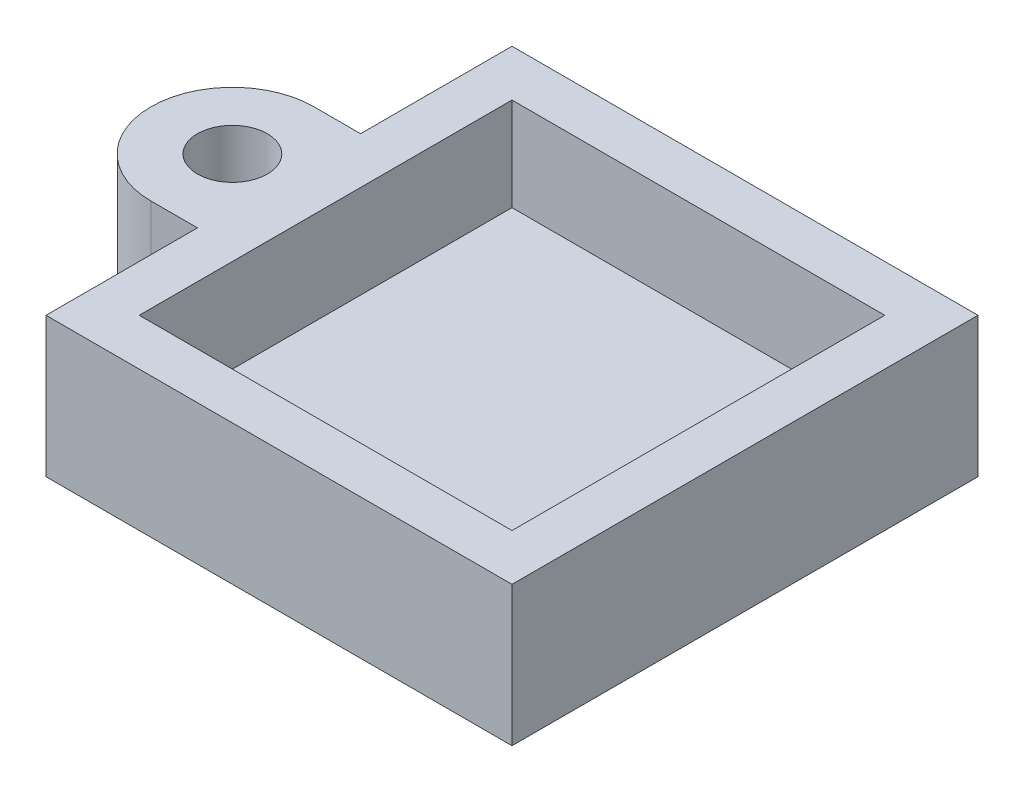
SolidWorks part; units mm, degrees
ref_plane "Front Plane" through (0, 0, 0) normal (0, 0, 1) x (1, 0, 0)
ref_plane "Top Plane" through (0, 0, 0) normal (0, 1, 0) x (1, 0, 0)
ref_plane "Right Plane" through (0, 0, 0) normal (1, 0, 0) x (0, 0, -1)
sketch "Sketch1" plane through (0, 0, 0) normal (0, 1, 0) x (1, 0, 0)
  line L0 (-2, 8) -> (-2.5, 8) construction
  line L1 (0, 0) -> (16, 0)
  line L2 (0, 0) -> (0, 16)
  line L3 (0, 16) -> (16, 16)
  line L4 (16, 0) -> (16, 16)
  line L5 (-2, 18) -> (18, 18)
  line L6 (-2, 18) -> (-2, 11.5)
  line L7 (-2, -2) -> (18, -2)
  line L8 (18, 18) -> (18, -2)
  line L9 (-2, 4.5) -> (-2, -2)
  line L10 (0, 8) -> (-0.5, 8) construction
  line L11 (-2, 8) -> (-7.5, 8) construction
  line L12 (0, 8) -> (-7.5, 8) construction
  line L13 (-4, 11.5) -> (-2, 11.5)
  line L14 (-4, 11.5) -> (-4, 4.5) construction
  line L15 (-4, 4.5) -> (-2, 4.5)
  circle A0 centre (-4, 8) radius 1.5
  arc A1 (-4, 11.5) -> (-4, 4.5) centre (-4, 8) ccw
  dimension "D7" = 3
  dimension "D9" = 7
  dimension "D1" = 16
  dimension "D2" = 16
  dimension "D3" = 2
  dimension "D4" = 2
  dimension "D5" = 2
  dimension "D6" = 2
  dimension "D8" = 2
extrude "Boss-Extrude1" add sketch "Sketch1" along normal blind 4
sketch "Sketch2" plane through (0, 0, 0) normal (0, -1, 0) x (1, 0, 0)
  line L0 (18, 2) -> (18, -18) construction
  line L1 (18, -18) -> (-2, -18) construction
  line L2 (-2, -18) -> (-2, -11.5) construction
  line L3 (-2, -11.5) -> (-4, -11.5) construction
  line L4 (-4, -4.5) -> (-2, -4.5) construction
  line L5 (-2, -4.5) -> (-2, 2) construction
  line L6 (-2, 2) -> (18, 2) construction
  line L7 (18, 2) -> (18, -18)
  line L8 (18, -18) -> (-2, -18)
  line L9 (-2, -18) -> (-2, -11.5)
  line L10 (-2, -11.5) -> (-4, -11.5)
  line L11 (-4, -4.5) -> (-2, -4.5)
  line L12 (-2, -4.5) -> (-2, 2)
  line L13 (-2, 2) -> (18, 2)
  arc A0 (-4, -4.5) -> (-4, -11.5) centre (-4, -8) ccw construction
  arc A1 (-4, -4.5) -> (-4, -11.5) centre (-4, -8) ccw
extrude "Boss-Extrude2" add sketch "Sketch2" along normal blind 2
